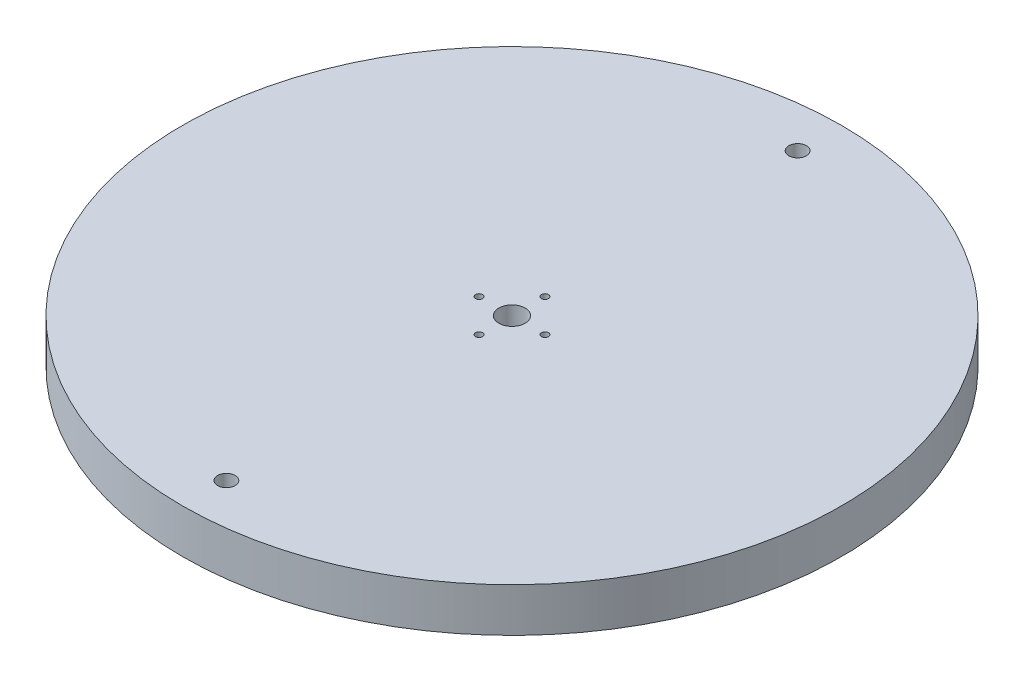
SolidWorks part; units mm, degrees
ref_plane "Plan de face" through (0, 0, 0) normal (0, 0, 1) x (1, 0, 0)
ref_plane "Plan de dessus" through (0, 0, 0) normal (0, 1, 0) x (1, 0, 0)
ref_plane "Plan de droite" through (0, 0, 0) normal (1, 0, 0) x (0, 0, -1)
sketch "Esquisse1" plane through (0, 0, 0) normal (0, 1, 0) x (1, 0, 0)
  circle A0 centre (0, 0) radius 75
  circle A1 centre (0, 0) radius 7.5
  circle A2 centre (0, -7.5) radius 0.8
  circle A3 centre (-7.5, 0) radius 0.8
  circle A4 centre (0, 7.5) radius 0.8
  circle A5 centre (7.5, 0) radius 0.8
  circle A6 centre (0, 0) radius 3
  circle A7 centre (0, 0) radius 65 construction
  circle A8 centre (0, 65) radius 2
  circle A9 centre (0, -65) radius 2
  point P15 (0, 0)
  point P22 (0, 0)
  dimension "D1" = 150
  dimension "D2" = 15
  dimension "D3" = 1.6
  dimension "D5" = 6
  dimension "D7" = 4
  dimension "D6" = 10
  dimension "D4" = 4
  dimension "D8" = 2
extrude "Boss.-Extru.1" add sketch "Esquisse1" along normal blind 10 contours A0 A9 A8 A5 A1 A2 A3 A4 | A5 A1 A4 A3 A2 A6
